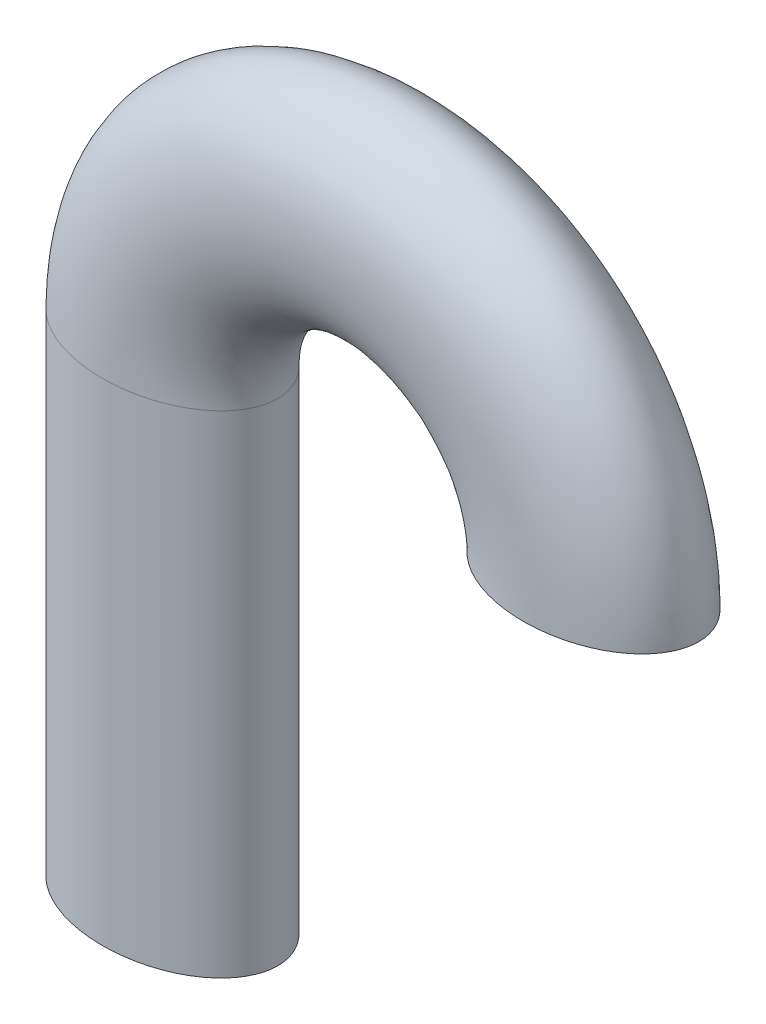
SolidWorks part; units mm, degrees
ref_plane "前视基准面" through (0, 0, 0) normal (0, 0, 1) x (1, 0, 0)
ref_plane "上视基准面" through (0, 0, 0) normal (0, 1, 0) x (1, 0, 0)
ref_plane "右视基准面" through (0, 0, 0) normal (1, 0, 0) x (0, 0, -1)
other "Configuration Table"
sketch "草图2" plane through (0, 0, 0) normal (0, 1, 0) x (1, 0, 0)
  ellipse E0 centre (0, 0) end of major axis (-6, 0) minor radius 4
  point P1 (0, 0)
  point P7 (0, 0)
  dimension "D1" = 8
  dimension "D2" = 6
sketch "草图3" plane through (0, 0, 0) normal (0, 0, 1) x (1, 0, 0)
  line L0 (0, 0) -> (0, 28)
  arc A0 (0, 28) -> (24, 28) centre (12, 28) cw
  dimension "D2" = 12
  dimension "D1" = 28
sweep "扫描2" add profiles "草图2" path "草图3"
